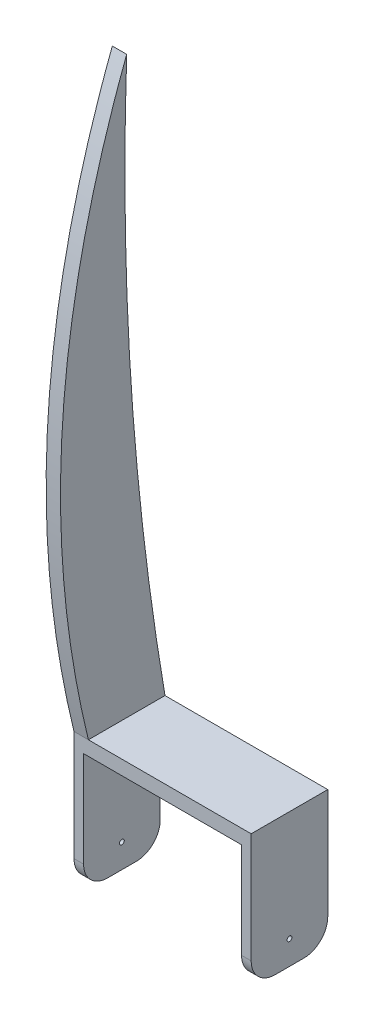
SolidWorks part; units mm, degrees
ref_plane "Front Plane" through (0, 0, 0) normal (0, 0, 1) x (1, 0, 0)
ref_plane "Top Plane" through (0, 0, 0) normal (0, 1, 0) x (1, 0, 0)
ref_plane "Right Plane" through (0, 0, 0) normal (1, 0, 0) x (0, 0, -1)
sketch "Sketch1" plane through (0, 0, 0) normal (0, 1, 0) x (1, 0, 0)
  line L1 (18.5, -8) -> (-18.5, -8)
  line L2 (18.5, -8) -> (18.5, 8)
  line L3 (18.5, 8) -> (-18.5, 8)
  line L4 (-18.5, -8) -> (-18.5, 8)
  line L5 (18.5, -8) -> (-18.5, 8) construction
  line L6 (18.5, 8) -> (-18.5, -8) construction
  point P0 (0, 0)
  dimension "D1" = 37
  dimension "D2" = 16
extrude "Boss-Extrude1" add sketch "Sketch1" along normal blind 3
sketch "Sketch2" plane through (0, 0, 0) normal (0, -1, 0) x (1, 0, 0)
  line L0 (-18.5, 8) -> (18.5, 8) construction
  line L1 (18.5, -8) -> (16.5, -8)
  line L2 (18.5, -8) -> (18.5, 8)
  line L3 (18.5, 8) -> (16.5, 8)
  line L4 (16.5, -8) -> (16.5, 8)
  line L6 (-18.5, -8) -> (-16.5, -8)
  line L7 (-18.5, -8) -> (-18.5, 8)
  line L8 (-18.5, 8) -> (-16.5, 8)
  line L9 (-16.5, -8) -> (-16.5, 8)
  dimension "D1" = 2
  dimension "D2" = 2
extrude "Boss-Extrude2" add sketch "Sketch2" along normal blind 25
fillet "Fillet1" radius 5 4 edges at (-17.5, -25, 8) (-17.5, -25, -8) (17.5, -25, 8) (17.5, -25, -8)
sketch "Sketch3" plane through (18.5, 0, 0) normal (1, 0, 0) x (0, 0, -1)
  line L0 (3, -25) -> (-3, -25) construction
  line L1 (-8, 3) -> (-8, -20) construction
  circle A0 centre (0, -20) radius 0.5
  dimension "D1" = 1
  dimension "D2" = 5
  dimension "D3" = 8
extrude "Cut-Extrude1" cut sketch "Sketch3" against normal through all both and the other way through all
sketch "Sketch4" plane through (-18.5, 0, 0) normal (-1, 0, 0) x (0, 0, 1)
  line L0 (0, -997) -> (0, 49003) construction
  line L1 (-8, 3) -> (8, 3) construction
  line L2 (-1000, 123) -> (49000, 123) construction
  line L3 (8, 3) -> (-8, 3)
  spline S0 degree 2 poles (8, 3) (22.7943, 63.3166) (0, 123) knots 0 0 0 1 1 1
  spline S1 degree 2 poles (-8, 3) (2.1387, 62.2723) (0, 123) knots 0 0 0 1 1 1
  point P6 (0, 3)
  dimension "D1" = 120
extrude "Boss-Extrude3" add sketch "Sketch4" against normal blind 3
